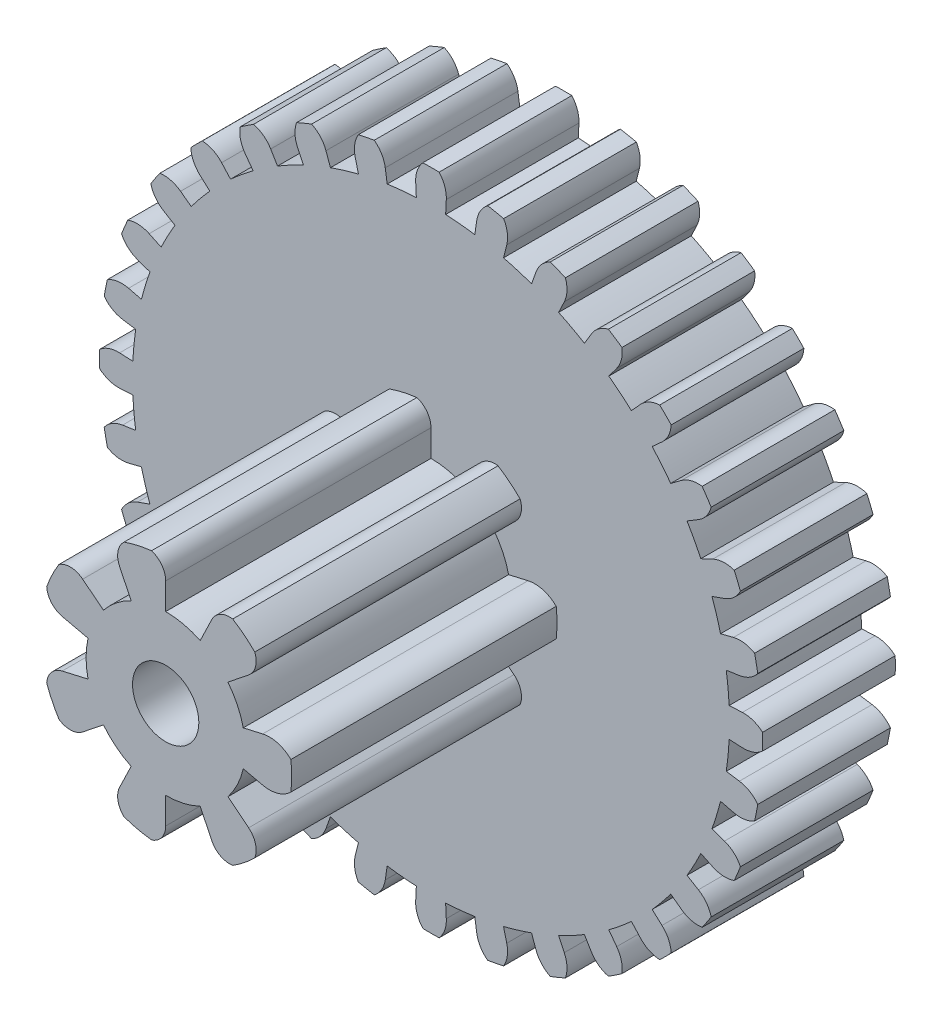
SolidWorks part; units mm, degrees
ref_plane "Front Plane" through (0, 0, 0) normal (0, 0, 1) x (1, 0, 0)
ref_plane "Top Plane" through (0, 0, 0) normal (0, 1, 0) x (1, 0, 0)
ref_plane "Right Plane" through (0, 0, 0) normal (1, 0, 0) x (0, 0, -1)
sketch "Sketch1" plane through (0, 0, 0) normal (0, 0, 1) x (1, 0, 0)
  line L0 (0, 0) -> (5.1564, 0) construction
  line L1 (0, 0) -> (4.4783, 0.4411) construction
  line L2 (0, 0) -> (5.5904, 0.2746) construction
  line L3 (0, 0) -> (5.5463, 0.1362) construction
  line L4 (4.4946, 0.2208) -> (4.6943, 0.2306)
  line L5 (4.4946, -0.2208) -> (4.6943, -0.2306)
  line L6 (4.4513, -0.6603) -> (4.6491, -0.6896)
  line L7 (4.3651, -1.0934) -> (4.5591, -1.142)
  line L8 (4.2369, -1.516) -> (4.4253, -1.5834)
  line L9 (4.068, -1.924) -> (4.2487, -2.0095)
  line L10 (3.8598, -2.3135) -> (4.0313, -2.4163)
  line L11 (3.6144, -2.6806) -> (3.7751, -2.7998)
  line L12 (3.3343, -3.022) -> (3.4825, -3.1563)
  line L13 (3.022, -3.3343) -> (3.1563, -3.4825)
  line L14 (2.6806, -3.6144) -> (2.7998, -3.7751)
  line L15 (2.3135, -3.8598) -> (2.4163, -4.0313)
  line L16 (1.924, -4.068) -> (2.0095, -4.2487)
  line L17 (1.516, -4.2369) -> (1.5834, -4.4253)
  line L18 (1.0934, -4.3651) -> (1.142, -4.5591)
  line L19 (0.6603, -4.4513) -> (0.6896, -4.6491)
  line L20 (0.2208, -4.4946) -> (0.2306, -4.6943)
  line L21 (-0.2208, -4.4946) -> (-0.2306, -4.6943)
  line L22 (-0.6603, -4.4513) -> (-0.6896, -4.6491)
  line L23 (-1.0934, -4.3651) -> (-1.142, -4.5591)
  line L24 (-1.516, -4.2369) -> (-1.5834, -4.4253)
  line L25 (-1.924, -4.068) -> (-2.0095, -4.2487)
  line L26 (-2.3135, -3.8598) -> (-2.4163, -4.0313)
  line L27 (-2.6806, -3.6144) -> (-2.7998, -3.7751)
  line L28 (-3.022, -3.3343) -> (-3.1563, -3.4825)
  line L29 (-3.3343, -3.022) -> (-3.4825, -3.1563)
  line L30 (-3.6144, -2.6806) -> (-3.7751, -2.7998)
  line L31 (-3.8598, -2.3135) -> (-4.0313, -2.4163)
  line L32 (-4.068, -1.924) -> (-4.2487, -2.0095)
  line L33 (-4.2369, -1.516) -> (-4.4253, -1.5834)
  line L34 (-4.3651, -1.0934) -> (-4.5591, -1.142)
  line L35 (-4.4513, -0.6603) -> (-4.6491, -0.6896)
  line L36 (-4.4946, -0.2208) -> (-4.6943, -0.2306)
  line L37 (-4.4946, 0.2208) -> (-4.6943, 0.2306)
  line L38 (-4.4513, 0.6603) -> (-4.6491, 0.6896)
  line L39 (-4.3651, 1.0934) -> (-4.5591, 1.142)
  line L40 (-4.2369, 1.516) -> (-4.4253, 1.5834)
  line L41 (-4.068, 1.924) -> (-4.2487, 2.0095)
  line L42 (-3.8598, 2.3135) -> (-4.0313, 2.4163)
  line L43 (-3.6144, 2.6806) -> (-3.7751, 2.7998)
  line L44 (-3.3343, 3.022) -> (-3.4825, 3.1563)
  line L45 (-3.022, 3.3343) -> (-3.1563, 3.4825)
  line L46 (-2.6806, 3.6144) -> (-2.7998, 3.7751)
  line L47 (-2.3135, 3.8598) -> (-2.4163, 4.0313)
  line L48 (-1.924, 4.068) -> (-2.0095, 4.2487)
  line L49 (-1.516, 4.2369) -> (-1.5834, 4.4253)
  line L50 (-1.0934, 4.3651) -> (-1.142, 4.5591)
  line L51 (-0.6603, 4.4513) -> (-0.6896, 4.6491)
  line L52 (-0.2208, 4.4946) -> (-0.2306, 4.6943)
  line L53 (0.2208, 4.4946) -> (0.2306, 4.6943)
  line L54 (0.6603, 4.4513) -> (0.6896, 4.6491)
  line L55 (1.0934, 4.3651) -> (1.142, 4.5591)
  line L56 (1.516, 4.2369) -> (1.5834, 4.4253)
  line L57 (1.924, 4.068) -> (2.0095, 4.2487)
  line L58 (2.3135, 3.8598) -> (2.4163, 4.0313)
  line L59 (2.6806, 3.6144) -> (2.7998, 3.7751)
  line L60 (3.022, 3.3343) -> (3.1563, 3.4825)
  line L61 (3.3343, 3.022) -> (3.4825, 3.1563)
  line L62 (3.6144, 2.6806) -> (3.7751, 2.7998)
  line L63 (3.8598, 2.3135) -> (4.0313, 2.4163)
  line L64 (4.068, 1.924) -> (4.2487, 2.0095)
  line L65 (4.2369, 1.516) -> (4.4253, 1.5834)
  line L66 (4.3651, 1.0934) -> (4.5591, 1.142)
  line L67 (4.4513, 0.6603) -> (4.6491, 0.6896)
  arc A0 (5, 0) -> (4.9965, -0.1859) centre (0, 0) ccw construction
  circle A1 centre (0, 0) radius 4.7 construction
  circle A2 centre (0, 0) radius 4.5 construction
  arc A4 (4.9985, 0.1227) -> (4.9985, -0.1227) centre (0, 0) cw
  arc A5 (4.4783, 0.4411) -> (4.4946, 0.2208) centre (0, 0) cw
  arc A6 (4.9985, 0.1227) -> (4.6943, 0.2306) centre (4.7152, -0.1933) ccw
  arc A7 (4.9985, -0.1227) -> (4.6943, -0.2306) centre (4.7152, 0.1933) cw
  arc A8 (4.4783, -0.4411) -> (4.4946, -0.2208) centre (0, 0) ccw
  arc A9 (4.4783, -0.4411) -> (4.4513, -0.6603) centre (0, 0) cw
  arc A10 (4.9264, -0.8548) -> (4.6491, -0.6896) centre (4.5869, -1.1095) ccw
  arc A11 (4.9264, -0.8548) -> (4.8785, -1.0955) centre (0, 0) cw
  arc A12 (4.8785, -1.0955) -> (4.5591, -1.142) centre (4.6623, -0.7303) cw
  arc A13 (4.3062, -1.3063) -> (4.3651, -1.0934) centre (0, 0) ccw
  arc A14 (4.3062, -1.3063) -> (4.2369, -1.516) centre (0, 0) cw
  arc A15 (4.665, -1.7995) -> (4.4253, -1.5834) centre (4.2823, -1.983) ccw
  arc A16 (4.665, -1.7995) -> (4.571, -2.0262) centre (0, 0) cw
  arc A17 (4.571, -2.0262) -> (4.2487, -2.0095) centre (4.4302, -1.6258) cw
  arc A18 (3.9686, -2.1213) -> (4.068, -1.924) centre (0, 0) ccw
  arc A19 (3.9686, -2.1213) -> (3.8598, -2.3135) centre (0, 0) cw
  arc A20 (4.2243, -2.675) -> (4.0313, -2.4163) centre (3.8131, -2.7803) ccw
  arc A21 (4.2243, -2.675) -> (4.0879, -2.879) centre (0, 0) cw
  arc A22 (4.0879, -2.879) -> (3.7751, -2.7998) centre (4.0279, -2.4589) cw
  arc A23 (3.4785, -2.8548) -> (3.6144, -2.6806) centre (0, 0) ccw
  arc A24 (3.4785, -2.8548) -> (3.3343, -3.022) centre (0, 0) cw
  arc A25 (3.6212, -3.4477) -> (3.4825, -3.1563) centre (3.1975, -3.4708) ccw
  arc A26 (3.6212, -3.4477) -> (3.4477, -3.6212) centre (0, 0) cw
  arc A27 (3.4477, -3.6212) -> (3.1563, -3.4825) centre (3.4708, -3.1975) cw
  arc A28 (2.8548, -3.4785) -> (3.022, -3.3343) centre (0, 0) ccw
  arc A29 (2.8548, -3.4785) -> (2.6806, -3.6144) centre (0, 0) cw
  arc A30 (2.879, -4.0879) -> (2.7998, -3.7751) centre (2.4589, -4.0279) ccw
  arc A31 (2.879, -4.0879) -> (2.675, -4.2243) centre (0, 0) cw
  arc A32 (2.675, -4.2243) -> (2.4163, -4.0313) centre (2.7803, -3.8131) cw
  arc A33 (2.1213, -3.9686) -> (2.3135, -3.8598) centre (0, 0) ccw
  arc A34 (2.1213, -3.9686) -> (1.924, -4.068) centre (0, 0) cw
  arc A35 (2.0262, -4.571) -> (2.0095, -4.2487) centre (1.6258, -4.4302) ccw
  arc A36 (2.0262, -4.571) -> (1.7995, -4.665) centre (0, 0) cw
  arc A37 (1.7995, -4.665) -> (1.5834, -4.4253) centre (1.983, -4.2823) cw
  arc A38 (1.3063, -4.3062) -> (1.516, -4.2369) centre (0, 0) ccw
  arc A39 (1.3063, -4.3062) -> (1.0934, -4.3651) centre (0, 0) cw
  arc A40 (1.0955, -4.8785) -> (1.142, -4.5591) centre (0.7303, -4.6623) ccw
  arc A41 (1.0955, -4.8785) -> (0.8548, -4.9264) centre (0, 0) cw
  arc A42 (0.8548, -4.9264) -> (0.6896, -4.6491) centre (1.1095, -4.5869) cw
  arc A43 (0.4411, -4.4783) -> (0.6603, -4.4513) centre (0, 0) ccw
  arc A44 (0.4411, -4.4783) -> (0.2208, -4.4946) centre (0, 0) cw
  arc A45 (0.1227, -4.9985) -> (0.2306, -4.6943) centre (-0.1933, -4.7152) ccw
  arc A46 (0.1227, -4.9985) -> (-0.1227, -4.9985) centre (0, 0) cw
  arc A47 (-0.1227, -4.9985) -> (-0.2306, -4.6943) centre (0.1933, -4.7152) cw
  arc A48 (-0.4411, -4.4783) -> (-0.2208, -4.4946) centre (0, 0) ccw
  arc A49 (-0.4411, -4.4783) -> (-0.6603, -4.4513) centre (0, 0) cw
  arc A50 (-0.8548, -4.9264) -> (-0.6896, -4.6491) centre (-1.1095, -4.5869) ccw
  arc A51 (-0.8548, -4.9264) -> (-1.0955, -4.8785) centre (0, 0) cw
  arc A52 (-1.0955, -4.8785) -> (-1.142, -4.5591) centre (-0.7303, -4.6623) cw
  arc A53 (-1.3063, -4.3062) -> (-1.0934, -4.3651) centre (0, 0) ccw
  arc A54 (-1.3063, -4.3062) -> (-1.516, -4.2369) centre (0, 0) cw
  arc A55 (-1.7995, -4.665) -> (-1.5834, -4.4253) centre (-1.983, -4.2823) ccw
  arc A56 (-1.7995, -4.665) -> (-2.0262, -4.571) centre (0, 0) cw
  arc A57 (-2.0262, -4.571) -> (-2.0095, -4.2487) centre (-1.6258, -4.4302) cw
  arc A58 (-2.1213, -3.9686) -> (-1.924, -4.068) centre (0, 0) ccw
  arc A59 (-2.1213, -3.9686) -> (-2.3135, -3.8598) centre (0, 0) cw
  arc A60 (-2.675, -4.2243) -> (-2.4163, -4.0313) centre (-2.7803, -3.8131) ccw
  arc A61 (-2.675, -4.2243) -> (-2.879, -4.0879) centre (0, 0) cw
  arc A62 (-2.879, -4.0879) -> (-2.7998, -3.7751) centre (-2.4589, -4.0279) cw
  arc A63 (-2.8548, -3.4785) -> (-2.6806, -3.6144) centre (0, 0) ccw
  arc A64 (-2.8548, -3.4785) -> (-3.022, -3.3343) centre (0, 0) cw
  arc A65 (-3.4477, -3.6212) -> (-3.1563, -3.4825) centre (-3.4708, -3.1975) ccw
  arc A66 (-3.4477, -3.6212) -> (-3.6212, -3.4477) centre (0, 0) cw
  arc A67 (-3.6212, -3.4477) -> (-3.4825, -3.1563) centre (-3.1975, -3.4708) cw
  arc A68 (-3.4785, -2.8548) -> (-3.3343, -3.022) centre (0, 0) ccw
  arc A69 (-3.4785, -2.8548) -> (-3.6144, -2.6806) centre (0, 0) cw
  arc A70 (-4.0879, -2.879) -> (-3.7751, -2.7998) centre (-4.0279, -2.4589) ccw
  arc A71 (-4.0879, -2.879) -> (-4.2243, -2.675) centre (0, 0) cw
  arc A72 (-4.2243, -2.675) -> (-4.0313, -2.4163) centre (-3.8131, -2.7803) cw
  arc A73 (-3.9686, -2.1213) -> (-3.8598, -2.3135) centre (0, 0) ccw
  arc A74 (-3.9686, -2.1213) -> (-4.068, -1.924) centre (0, 0) cw
  arc A75 (-4.571, -2.0262) -> (-4.2487, -2.0095) centre (-4.4302, -1.6258) ccw
  arc A76 (-4.571, -2.0262) -> (-4.665, -1.7995) centre (0, 0) cw
  arc A77 (-4.665, -1.7995) -> (-4.4253, -1.5834) centre (-4.2823, -1.983) cw
  arc A78 (-4.3062, -1.3063) -> (-4.2369, -1.516) centre (0, 0) ccw
  arc A79 (-4.3062, -1.3063) -> (-4.3651, -1.0934) centre (0, 0) cw
  arc A80 (-4.8785, -1.0955) -> (-4.5591, -1.142) centre (-4.6623, -0.7303) ccw
  arc A81 (-4.8785, -1.0955) -> (-4.9264, -0.8548) centre (0, 0) cw
  arc A82 (-4.9264, -0.8548) -> (-4.6491, -0.6896) centre (-4.5869, -1.1095) cw
  arc A83 (-4.4783, -0.4411) -> (-4.4513, -0.6603) centre (0, 0) ccw
  arc A84 (-4.4783, -0.4411) -> (-4.4946, -0.2208) centre (0, 0) cw
  arc A85 (-4.9985, -0.1227) -> (-4.6943, -0.2306) centre (-4.7152, 0.1933) ccw
  arc A86 (-4.9985, -0.1227) -> (-4.9985, 0.1227) centre (0, 0) cw
  arc A87 (-4.9985, 0.1227) -> (-4.6943, 0.2306) centre (-4.7152, -0.1933) cw
  arc A88 (-4.4783, 0.4411) -> (-4.4946, 0.2208) centre (0, 0) ccw
  arc A89 (-4.4783, 0.4411) -> (-4.4513, 0.6603) centre (0, 0) cw
  arc A90 (-4.9264, 0.8548) -> (-4.6491, 0.6896) centre (-4.5869, 1.1095) ccw
  arc A91 (-4.9264, 0.8548) -> (-4.8785, 1.0955) centre (0, 0) cw
  arc A92 (-4.8785, 1.0955) -> (-4.5591, 1.142) centre (-4.6623, 0.7303) cw
  arc A93 (-4.3062, 1.3063) -> (-4.3651, 1.0934) centre (0, 0) ccw
  arc A94 (-4.3062, 1.3063) -> (-4.2369, 1.516) centre (0, 0) cw
  arc A95 (-4.665, 1.7995) -> (-4.4253, 1.5834) centre (-4.2823, 1.983) ccw
  arc A96 (-4.665, 1.7995) -> (-4.571, 2.0262) centre (0, 0) cw
  arc A97 (-4.571, 2.0262) -> (-4.2487, 2.0095) centre (-4.4302, 1.6258) cw
  arc A98 (-3.9686, 2.1213) -> (-4.068, 1.924) centre (0, 0) ccw
  arc A99 (-3.9686, 2.1213) -> (-3.8598, 2.3135) centre (0, 0) cw
  arc A100 (-4.2243, 2.675) -> (-4.0313, 2.4163) centre (-3.8131, 2.7803) ccw
  arc A101 (-4.2243, 2.675) -> (-4.0879, 2.879) centre (0, 0) cw
  arc A102 (-4.0879, 2.879) -> (-3.7751, 2.7998) centre (-4.0279, 2.4589) cw
  arc A103 (-3.4785, 2.8548) -> (-3.6144, 2.6806) centre (0, 0) ccw
  arc A104 (-3.4785, 2.8548) -> (-3.3343, 3.022) centre (0, 0) cw
  arc A105 (-3.6212, 3.4477) -> (-3.4825, 3.1563) centre (-3.1975, 3.4708) ccw
  arc A106 (-3.6212, 3.4477) -> (-3.4477, 3.6212) centre (0, 0) cw
  arc A107 (-3.4477, 3.6212) -> (-3.1563, 3.4825) centre (-3.4708, 3.1975) cw
  arc A108 (-2.8548, 3.4785) -> (-3.022, 3.3343) centre (0, 0) ccw
  arc A109 (-2.8548, 3.4785) -> (-2.6806, 3.6144) centre (0, 0) cw
  arc A110 (-2.879, 4.0879) -> (-2.7998, 3.7751) centre (-2.4589, 4.0279) ccw
  arc A111 (-2.879, 4.0879) -> (-2.675, 4.2243) centre (0, 0) cw
  arc A112 (-2.675, 4.2243) -> (-2.4163, 4.0313) centre (-2.7803, 3.8131) cw
  arc A113 (-2.1213, 3.9686) -> (-2.3135, 3.8598) centre (0, 0) ccw
  arc A114 (-2.1213, 3.9686) -> (-1.924, 4.068) centre (0, 0) cw
  arc A115 (-2.0262, 4.571) -> (-2.0095, 4.2487) centre (-1.6258, 4.4302) ccw
  arc A116 (-2.0262, 4.571) -> (-1.7995, 4.665) centre (0, 0) cw
  arc A117 (-1.7995, 4.665) -> (-1.5834, 4.4253) centre (-1.983, 4.2823) cw
  arc A118 (-1.3063, 4.3062) -> (-1.516, 4.2369) centre (0, 0) ccw
  arc A119 (-1.3063, 4.3062) -> (-1.0934, 4.3651) centre (0, 0) cw
  arc A120 (-1.0955, 4.8785) -> (-1.142, 4.5591) centre (-0.7303, 4.6623) ccw
  arc A121 (-1.0955, 4.8785) -> (-0.8548, 4.9264) centre (0, 0) cw
  arc A122 (-0.8548, 4.9264) -> (-0.6896, 4.6491) centre (-1.1095, 4.5869) cw
  arc A123 (-0.4411, 4.4783) -> (-0.6603, 4.4513) centre (0, 0) ccw
  arc A124 (-0.4411, 4.4783) -> (-0.2208, 4.4946) centre (0, 0) cw
  arc A125 (-0.1227, 4.9985) -> (-0.2306, 4.6943) centre (0.1933, 4.7152) ccw
  arc A126 (-0.1227, 4.9985) -> (0.1227, 4.9985) centre (0, 0) cw
  arc A127 (0.1227, 4.9985) -> (0.2306, 4.6943) centre (-0.1933, 4.7152) cw
  arc A128 (0.4411, 4.4783) -> (0.2208, 4.4946) centre (0, 0) ccw
  arc A129 (0.4411, 4.4783) -> (0.6603, 4.4513) centre (0, 0) cw
  arc A130 (0.8548, 4.9264) -> (0.6896, 4.6491) centre (1.1095, 4.5869) ccw
  arc A131 (0.8548, 4.9264) -> (1.0955, 4.8785) centre (0, 0) cw
  arc A132 (1.0955, 4.8785) -> (1.142, 4.5591) centre (0.7303, 4.6623) cw
  arc A133 (1.3063, 4.3062) -> (1.0934, 4.3651) centre (0, 0) ccw
  arc A134 (1.3063, 4.3062) -> (1.516, 4.2369) centre (0, 0) cw
  arc A135 (1.7995, 4.665) -> (1.5834, 4.4253) centre (1.983, 4.2823) ccw
  arc A136 (1.7995, 4.665) -> (2.0262, 4.571) centre (0, 0) cw
  arc A137 (2.0262, 4.571) -> (2.0095, 4.2487) centre (1.6258, 4.4302) cw
  arc A138 (2.1213, 3.9686) -> (1.924, 4.068) centre (0, 0) ccw
  arc A139 (2.1213, 3.9686) -> (2.3135, 3.8598) centre (0, 0) cw
  arc A140 (2.675, 4.2243) -> (2.4163, 4.0313) centre (2.7803, 3.8131) ccw
  arc A141 (2.675, 4.2243) -> (2.879, 4.0879) centre (0, 0) cw
  arc A142 (2.879, 4.0879) -> (2.7998, 3.7751) centre (2.4589, 4.0279) cw
  arc A143 (2.8548, 3.4785) -> (2.6806, 3.6144) centre (0, 0) ccw
  arc A144 (2.8548, 3.4785) -> (3.022, 3.3343) centre (0, 0) cw
  arc A145 (3.4477, 3.6212) -> (3.1563, 3.4825) centre (3.4708, 3.1975) ccw
  arc A146 (3.4477, 3.6212) -> (3.6212, 3.4477) centre (0, 0) cw
  arc A147 (3.6212, 3.4477) -> (3.4825, 3.1563) centre (3.1975, 3.4708) cw
  arc A148 (3.4785, 2.8548) -> (3.3343, 3.022) centre (0, 0) ccw
  arc A149 (3.4785, 2.8548) -> (3.6144, 2.6806) centre (0, 0) cw
  arc A150 (4.0879, 2.879) -> (3.7751, 2.7998) centre (4.0279, 2.4589) ccw
  arc A151 (4.0879, 2.879) -> (4.2243, 2.675) centre (0, 0) cw
  arc A152 (4.2243, 2.675) -> (4.0313, 2.4163) centre (3.8131, 2.7803) cw
  arc A153 (3.9686, 2.1213) -> (3.8598, 2.3135) centre (0, 0) ccw
  arc A154 (3.9686, 2.1213) -> (4.068, 1.924) centre (0, 0) cw
  arc A155 (4.571, 2.0262) -> (4.2487, 2.0095) centre (4.4302, 1.6258) ccw
  arc A156 (4.571, 2.0262) -> (4.665, 1.7995) centre (0, 0) cw
  arc A157 (4.665, 1.7995) -> (4.4253, 1.5834) centre (4.2823, 1.983) cw
  arc A158 (4.3062, 1.3063) -> (4.2369, 1.516) centre (0, 0) ccw
  arc A159 (4.3062, 1.3063) -> (4.3651, 1.0934) centre (0, 0) cw
  arc A160 (4.8785, 1.0955) -> (4.5591, 1.142) centre (4.6623, 0.7303) ccw
  arc A161 (4.8785, 1.0955) -> (4.9264, 0.8548) centre (0, 0) cw
  arc A162 (4.9264, 0.8548) -> (4.6491, 0.6896) centre (4.5869, 1.1095) cw
  arc A163 (4.4783, 0.4411) -> (4.4513, 0.6603) centre (0, 0) ccw
  point P333 (0, 0)
  dimension "D1" = 10
  dimension "D2" = 0.5
  dimension "D3" = 9.4
  dimension "D4" = 5.625
  dimension "D5" = 2.813
  dimension "D6" = 1.406
  dimension "D7" = 32
extrude "Boss-Extrude1" add sketch "Sketch1" along normal blind 2 contours A5 A163 L67 A162 A161 A160 L66 A159 A158 L65 A157 A156 A155 L64 A154 A153 L63 A152 A151 A150 L62 A149 A148 L61 A147 A146 A145 L60 A144 A143 L59 A142 A141 A140 L58 A139 A138 L57 A137 A136 A135 L56 A134 A133 L55 A132 A131 A130 L54 A129 A128
sketch "Sketch2" plane through (0, 0, 2) normal (0, 0, 1) x (1, 0, 0)
  line L0 (1.1699, 0.267) -> (1.4624, 0.3338)
  line L1 (3.0757, 0) -> (0, 0) construction
  line L2 (0, 0) -> (1.0812, 0.5207) construction
  line L3 (0, 0) -> (3.0279, 0.6911) construction
  line L4 (0, 0) -> (3.0638, 0.3452) construction
  line L5 (1.1699, -0.267) -> (1.4624, -0.3338)
  line L6 (0.9382, -0.7482) -> (1.2509, -0.9976)
  line L7 (0.5207, -1.0812) -> (0.6942, -1.4415)
  line L8 (0, -1.2) -> (0, -1.6)
  line L9 (-0.5207, -1.0812) -> (-0.6942, -1.4416)
  line L10 (-0.9382, -0.7482) -> (-1.2509, -0.9976)
  line L11 (-1.1699, -0.267) -> (-1.5599, -0.356)
  line L12 (-1.1699, 0.267) -> (-1.5599, 0.356)
  line L13 (-0.9382, 0.7482) -> (-1.2509, 0.9976)
  line L14 (-0.5207, 1.0812) -> (-0.6942, 1.4416)
  line L15 (0, 1.2) -> (0, 1.6)
  line L16 (0.5207, 1.0812) -> (0.6942, 1.4415)
  line L17 (0.9382, 0.7482) -> (1.2509, 0.9976)
  circle A0 centre (0, 0) radius 1.9 construction
  circle A1 centre (0, 0) radius 1.5 construction
  circle A2 centre (0, 0) radius 1.2 construction
  arc A3 (1.0812, 0.5207) -> (1.1699, 0.267) centre (0, 0) cw
  arc A4 (1.4624, 0.3338) -> (1.8881, 0.2127) centre (1.5648, -0.115) cw
  arc A5 (1.8881, 0.2127) -> (1.8881, -0.2127) centre (0, 0) cw
  arc A6 (1.4624, -0.3338) -> (1.8881, -0.2127) centre (1.5648, 0.115) ccw
  arc A7 (1.0812, -0.5207) -> (1.1699, -0.267) centre (0, 0) ccw
  arc A8 (1.0812, -0.5207) -> (0.9382, -0.7482) centre (0, 0) cw
  arc A9 (1.2509, -0.9976) -> (1.3435, -1.3435) centre (1.063, -1.2332) cw
  arc A10 (1.3435, -1.3435) -> (1.0109, -1.6088) centre (0, 0) cw
  arc A11 (0.6942, -1.4415) -> (1.0109, -1.6088) centre (0.9658, -1.3108) ccw
  arc A12 (0.267, -1.1699) -> (0.5207, -1.0812) centre (0, 0) ccw
  arc A13 (0.267, -1.1699) -> (0, -1.2) centre (0, 0) cw
  arc A14 (0, -1.6) -> (-0.2127, -1.8881) centre (-0.3014, -1.6) cw
  arc A15 (-0.2127, -1.8881) -> (-0.6275, -1.7934) centre (0, 0) cw
  arc A16 (-0.6942, -1.4416) -> (-0.6275, -1.7934) centre (-0.4227, -1.5723) ccw
  arc A17 (-0.7482, -0.9382) -> (-0.5207, -1.0812) centre (0, 0) ccw
  arc A18 (-0.7482, -0.9382) -> (-0.9382, -0.7482) centre (0, 0) cw
  arc A19 (-1.2509, -0.9976) -> (-1.6088, -1.0109) centre (-1.4388, -0.7619) cw
  arc A20 (-1.6088, -1.0109) -> (-1.7934, -0.6275) centre (0, 0) cw
  arc A21 (-1.5599, -0.356) -> (-1.7934, -0.6275) centre (-1.4928, -0.6499) ccw
  arc A22 (-1.2, 0) -> (-1.1699, -0.267) centre (0, 0) ccw
  arc A23 (-1.2, 0) -> (-1.1699, 0.267) centre (0, 0) cw
  arc A24 (-1.5599, 0.356) -> (-1.7934, 0.6275) centre (-1.4928, 0.6499) cw
  arc A25 (-1.7934, 0.6275) -> (-1.6088, 1.0109) centre (0, 0) cw
  arc A26 (-1.2509, 0.9976) -> (-1.6088, 1.0109) centre (-1.4388, 0.7619) ccw
  arc A27 (-0.7482, 0.9382) -> (-0.9382, 0.7482) centre (0, 0) ccw
  arc A28 (-0.7482, 0.9382) -> (-0.5207, 1.0812) centre (0, 0) cw
  arc A29 (-0.6942, 1.4416) -> (-0.6275, 1.7934) centre (-0.4227, 1.5723) cw
  arc A30 (-0.6275, 1.7934) -> (-0.2127, 1.8881) centre (0, 0) cw
  arc A31 (0, 1.6) -> (-0.2127, 1.8881) centre (-0.3014, 1.6) ccw
  arc A32 (0.267, 1.1699) -> (0, 1.2) centre (0, 0) ccw
  arc A33 (0.267, 1.1699) -> (0.5207, 1.0812) centre (0, 0) cw
  arc A34 (0.6942, 1.4415) -> (1.0109, 1.6088) centre (0.9658, 1.3108) cw
  arc A35 (1.0109, 1.6088) -> (1.3435, 1.3435) centre (0, 0) cw
  arc A36 (1.2509, 0.9976) -> (1.3435, 1.3435) centre (1.063, 1.2332) ccw
  arc A37 (1.0812, 0.5207) -> (0.9382, 0.7482) centre (0, 0) ccw
  point P82 (0, 0)
  dimension "D1" = 3.8
  dimension "D2" = 3
  dimension "D3" = 0.7
  dimension "D4" = 25.714
  dimension "D5" = 12.857
  dimension "D6" = 6.429
extrude "Boss-Extrude2" add sketch "Sketch2" along normal blind 4 contours A3 A37 L17 A36 A35 A34 L16 A33 A32 L15 A31 A30 A29 L14 A28 A27 L13 A26 A25 A24 L12 A23 A22 L11 A21 A20 A19 L10 A18 A17 L9 A16 A15 A14 L8 A13 A12 L7 A11 A10 A9 L6 A8 A7 L5 A6 A5 A4 L0
sketch "Sketch3" plane through (0, 0, 6) normal (0, 0, 1) x (1, 0, 0)
  circle A0 centre (0, 0) radius 0.5
  dimension "D1" = 1
extrude "Cut-Extrude1" cut sketch "Sketch3" against normal blind 6
